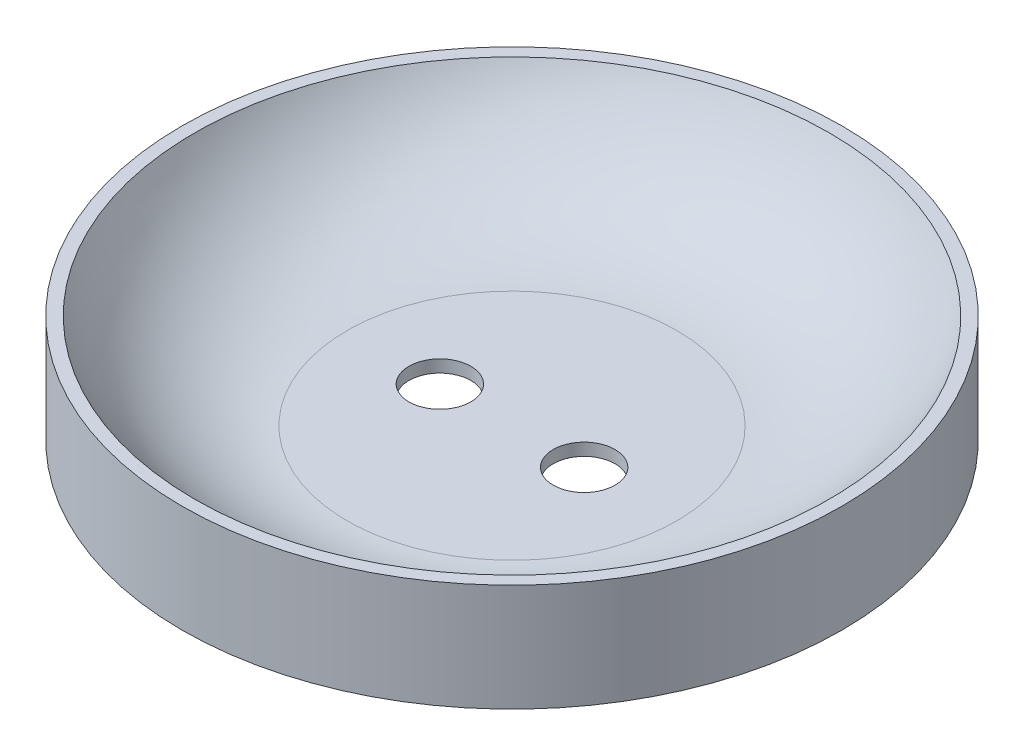
SolidWorks part; units mm, degrees
ref_plane "Front" through (0, 0, 0) normal (0, 0, 1) x (1, 0, 0)
ref_plane "Top" through (0, 0, 0) normal (0, 1, 0) x (1, 0, 0)
ref_plane "Right" through (0, 0, 0) normal (1, 0, 0) x (0, 0, -1)
sketch "Sketch1" plane through (0, 0, 0) normal (0, 0, 1) x (1, 0, 0)
  line L0 (0, 0) -> (0, 25.4) construction
  line L1 (-101.6, 0) -> (101.6, 0) construction
  line L2 (-101.6, 0) -> (-101.6, 25.4) construction
  line L3 (-101.6, 25.4) -> (101.6, 25.4) construction
  line L4 (101.6, 0) -> (101.6, 25.4) construction
  line L5 (0, 0) -> (50.8, 0)
  line L6 (97.79, 25.4) -> (97.79, 3.81)
  line L7 (97.79, 3.81) -> (78.74, 3.81)
  line L8 (0, 3.81) -> (50.8, 3.81)
  line L9 (101.6, 33.0776) -> (101.6, 0)
  line L10 (101.6, 0) -> (78.74, 0)
  line L11 (97.79, 33.0776) -> (101.6, 33.0776)
  line L12 (78.74, 3.81) -> (78.74, 0)
  line L13 (101.6, 43.4975) -> (101.6, 0) construction
  line L14 (0, 3.81) -> (0, 0)
  arc A0 (50.8, 0) -> (97.79, 25.4) centre (50.8, 56.1658) ccw
  arc A1 (50.8, 3.81) -> (97.79, 33.0776) centre (50.8, 56.1658) ccw
  arc A3 (50.8, 3.81) -> (101.6, 43.4975) centre (50.8, 56.1658) ccw construction
  dimension "D4" = 3.81
  dimension "D1" = 203.2
  dimension "D2" = 25.4
  dimension "D3" = 50.8
  dimension "D5" = 3.81
  dimension "D6" = 19.05
  dimension "D7" = 3.81
revolve "Revolve1" add sketch "Sketch1" angle 360 about L0
sketch "Sketch2" plane through (0, 0, 0) normal (0, -1, 0) x (1, 0, 0)
  line L0 (-22.225, 0) -> (22.225, 0) construction
  circle A0 centre (-22.225, 0) radius 9.525
  circle A1 centre (22.225, 0) radius 9.525
  dimension "D2" = 19.05
  dimension "D1" = 44.45
extrude "Cut-Extrude1" cut sketch "Sketch2" against normal through all
sketch "Sketch3" plane through (0, 0, 0) normal (0, -1, 0) x (1, 0, 0)
  line L0 (0, 0) -> (-88.9, 0) construction
  circle A0 centre (-88.9, 0) radius 6.35
  dimension "D2" = 12.7
  dimension "D1" = 88.9
extrude "Cut-Extrude2" cut sketch "Sketch3" against normal up to surface (3.81 mm away) up to face at (0, 3.81, -78.74)
pattern_circular "CirPattern1" count 15 over 360 about axis through (0, 0, 0) along (0, 1, 0) of "Cut-Extrude2"
fillet "Fillet1" radius 1.27 2 edges at (0, 3.81, -78.74) (0, 3.81, -97.79)
